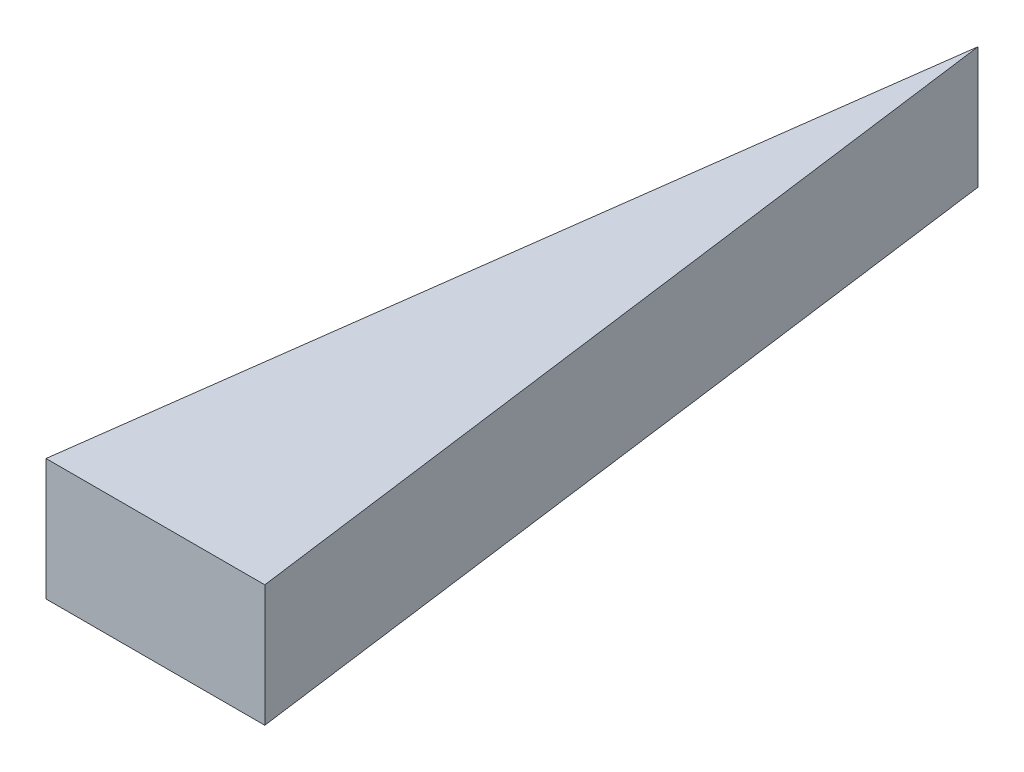
SolidWorks part; units mm, degrees
material "AISI 4340 Steel, annealed"
ref_plane "Front Plane" through (0, 0, 0) normal (0, 0, 1) x (1, 0, 0)
ref_plane "Top Plane" through (0, 0, 0) normal (0, 1, 0) x (1, 0, 0)
ref_plane "Right Plane" through (0, 0, 0) normal (1, 0, 0) x (0, 0, -1)
sketch "Sketch1" plane through (0, 0, 0) normal (0, 1, 0) x (1, 0, 0)
  line L0 (0, 0) -> (-117.055, -880.231)
  line L1 (-117.055, -880.231) -> (117.055, -880.231)
  line L2 (117.055, -880.231) -> (0, 0)
  point P3 (0, -880.231)
  dimension "D1" = 887.98
  dimension "D2" = 234.11
extrude "Main extrude" add sketch "Sketch1" along normal mid plane 130.18
shell "Shell1" thickness 5
